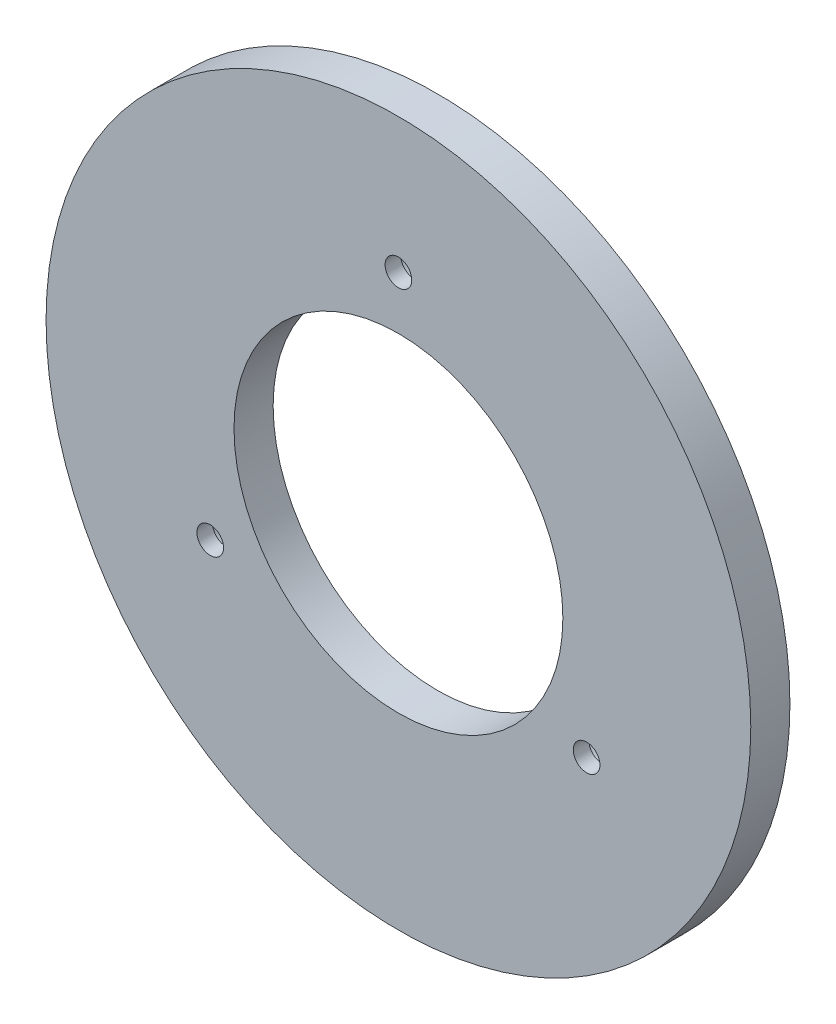
SolidWorks part; units mm, degrees
material "7075-O (SS)"
ref_plane "Front" through (0, 0, 0) normal (0, 0, 1) x (1, 0, 0)
ref_plane "Top" through (0, 0, 0) normal (0, 1, 0) x (1, 0, 0)
ref_plane "Right" through (0, 0, 0) normal (1, 0, 0) x (0, 0, -1)
sketch "Croquis1" plane through (0, 0, 0) normal (0, 0, 1) x (1, 0, 0)
  circle A0 centre (0, 0) radius 45
  circle A1 centre (0, 0) radius 21
  dimension "D1" = 90
  dimension "D2" = 42
extrude "Saliente-Extruir1" add sketch "Croquis1" along normal blind 5
hole_wizard "Taladro de margen para M31" positions "Croquis2" profile "Croquis3" hole size "M3" standard "Ansi Metric" end condition up to next
sketch "Croquis2" plane through (0, 0, 0) normal (0, 0, -1) x (-1, 0, 0)
  line L0 (0, 2.75) -> (0, -2.75) construction
  line L1 (2.75, 0) -> (-2.75, 0) construction
  point P0 (0, 27.75)
  point P11 (24.0322, -13.875)
  point P12 (-24.0322, -13.875)
  dimension "D1" = 27.75
  dimension "D2" = 3
sketch "Croquis3" plane through (0, 27.75, 0) normal (1, 0, 0) x (0, 1, 0)
  line L0 (0, 0) -> (0, 5)
  line L1 (0, 5) -> (1.7, 5)
  line L2 (1.7, 5) -> (1.7, 0)
  line L5 (1.7, 0) -> (0, 0)
  line L11 (0, -6.35) -> (0, 107.95) construction
  dimension "Diámetro de taladro hasta el siguiente" = 3.4
  dimension "Profundidad de taladro hasta el siguiente" = 5
sketch "Croquis4" plane through (0, 0, 0) normal (0, 0, -1) x (-1, 0, 0)
  circle A0 centre (0, 27.75) radius 3.2
  circle A1 centre (23.3827, -13.5) radius 3.2
  circle A2 centre (-24.0322, -13.125) radius 3.2
  dimension "D1" = 6.4
  dimension "D2" = 3
extrude "Cortar-Extruir1" cut sketch "Croquis4" against normal blind 3
